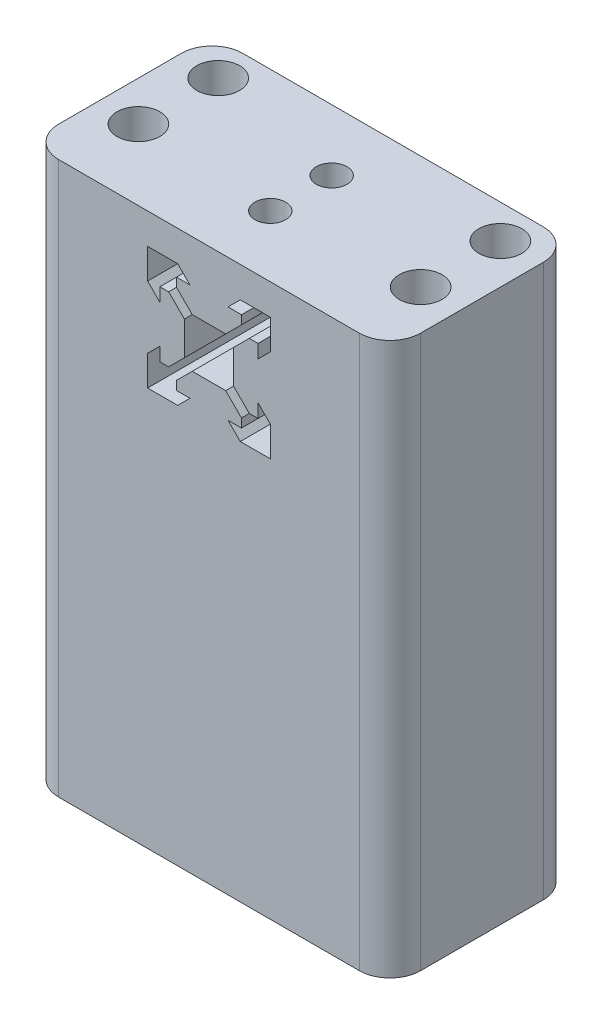
SolidWorks part; units mm, degrees
ref_plane "Front Plane" through (0, 0, 0) normal (0, 0, 1) x (1, 0, 0)
ref_plane "Top Plane" through (0, 0, 0) normal (0, 1, 0) x (1, 0, 0)
ref_plane "Right Plane" through (0, 0, 0) normal (1, 0, 0) x (0, 0, -1)
sketch "Sketch1" plane through (0, 0, 0) normal (0, 0, 1) x (1, 0, 0)
  line L1 (-29.5, 15) -> (29.5, 15)
  line L2 (-29.5, 15) -> (-29.5, -15)
  line L3 (-29.5, -15) -> (29.5, -15)
  line L4 (29.5, 15) -> (29.5, -15)
  line L5 (-29.5, 15) -> (29.5, -15) construction
  line L6 (-29.5, -15) -> (29.5, 15) construction
  line L90 (4, 2.7272) -> (6.5728, 5.3)
  line L91 (6.5728, 5.3) -> (8, 5.3)
  line L92 (8, 5.3) -> (8, 3.1)
  line L93 (8, 3.1) -> (10, 5.1)
  line L94 (10, 5.1) -> (10, 10)
  line L95 (10, 10) -> (5.1, 10)
  line L96 (5.1, 10) -> (3.1, 8)
  line L97 (3.1, 8) -> (5.3, 8)
  line L98 (5.3, 8) -> (5.3, 6.5728)
  line L99 (5.3, 6.5728) -> (2.7272, 4)
  line L100 (2.7272, 4) -> (-2.7272, 4)
  line L101 (-2.7272, 4) -> (-5.3, 6.5728)
  line L102 (-5.3, 6.5728) -> (-5.3, 8)
  line L103 (-5.3, 8) -> (-3.1, 8)
  line L104 (-3.1, 8) -> (-5.1, 10)
  line L105 (-5.1, 10) -> (-10, 10)
  line L106 (-10, 10) -> (-10, 5.1)
  line L107 (-10, 5.1) -> (-8, 3.1)
  line L108 (-8, 3.1) -> (-8, 5.3)
  line L109 (-8, 5.3) -> (-6.5728, 5.3)
  line L110 (-6.5728, 5.3) -> (-4, 2.7272)
  line L111 (-4, 2.7272) -> (-4, -2.7272)
  line L112 (-4, -2.7272) -> (-6.5728, -5.3)
  line L113 (-6.5728, -5.3) -> (-8, -5.3)
  line L114 (-8, -5.3) -> (-8, -3.1)
  line L115 (-8, -3.1) -> (-10, -5.1)
  line L116 (-10, -5.1) -> (-10, -10)
  line L117 (-10, -10) -> (-5.1, -10)
  line L118 (-5.1, -10) -> (-3.1, -8)
  line L119 (-3.1, -8) -> (-5.3, -8)
  line L120 (-5.3, -8) -> (-5.3, -6.5728)
  line L121 (-5.3, -6.5728) -> (-2.7272, -4)
  line L122 (-2.7272, -4) -> (2.7272, -4)
  line L123 (2.7272, -4) -> (5.3, -6.5728)
  line L124 (5.3, -6.5728) -> (5.3, -8)
  line L125 (5.3, -8) -> (3.1, -8)
  line L126 (3.1, -8) -> (5.1, -10)
  line L127 (5.1, -10) -> (10, -10)
  line L128 (10, -10) -> (10, -5.1)
  line L129 (10, -5.1) -> (8, -3.1)
  line L130 (8, -3.1) -> (8, -5.3)
  line L131 (8, -5.3) -> (6.5728, -5.3)
  line L132 (6.5728, -5.3) -> (4, -2.7272)
  line L133 (4, -2.7272) -> (4, 2.7272)
  point P2 (0, 0)
  dimension "D1" = 20
  dimension "D2" = 59
  dimension "D3" = 30
extrude "Boss-Extrude1" add sketch "Sketch1" against normal blind 30
sketch "Sketch2" plane through (0, 15, 0) normal (0, 1, 0) x (1, 0, 0)
  line L0 (-29.5, 30) -> (-29.5, 0) construction
  circle A0 centre (0, 10) radius 2.5
  circle A1 centre (0, 20) radius 2.5
  circle A2 centre (-23, 24.5) radius 3.5
  circle A4 centre (23, 24.5) radius 3.5
  circle A7 centre (23, 11.5) radius 3.5
  circle A9 centre (-23, 11.5) radius 3.5
  point P7 (0, 0)
  point P8 (0, 0)
  dimension "D1" = 10
  dimension "D3" = 46
  dimension "D2" = 10
  dimension "D4" = 13
  dimension "D5" = 6.5
  dimension "D6" = 5.5
extrude "Cut-Extrude1" cut sketch "Sketch2" against normal through all
sketch "Sketch3" plane through (0, 0, 0) normal (0, 0, 1) x (1, 0, 0)
  line L5 (-29.5, -15) -> (29.5, -15)
  line L7 (-29.5, -15) -> (-29.5, -75)
  line L8 (29.5, -15) -> (29.5, -75)
  line L9 (-29.5, -75) -> (29.5, -75)
  dimension "D4" = 60
extrude "Boss-Extrude2" add sketch "Sketch3" against normal up to surface (30 mm away) up to face at (0, 0, -30)
fillet "Fillet1" radius 5 1 edges at (29.5, -30, 0)
fillet "Fillet2" radius 5 1 edges at (29.5, -30, -30)
fillet "Fillet3" radius 5 1 edges at (-29.5, -30, -30)
fillet "Fillet4" radius 5 1 edges at (-29.5, -30, 0)
